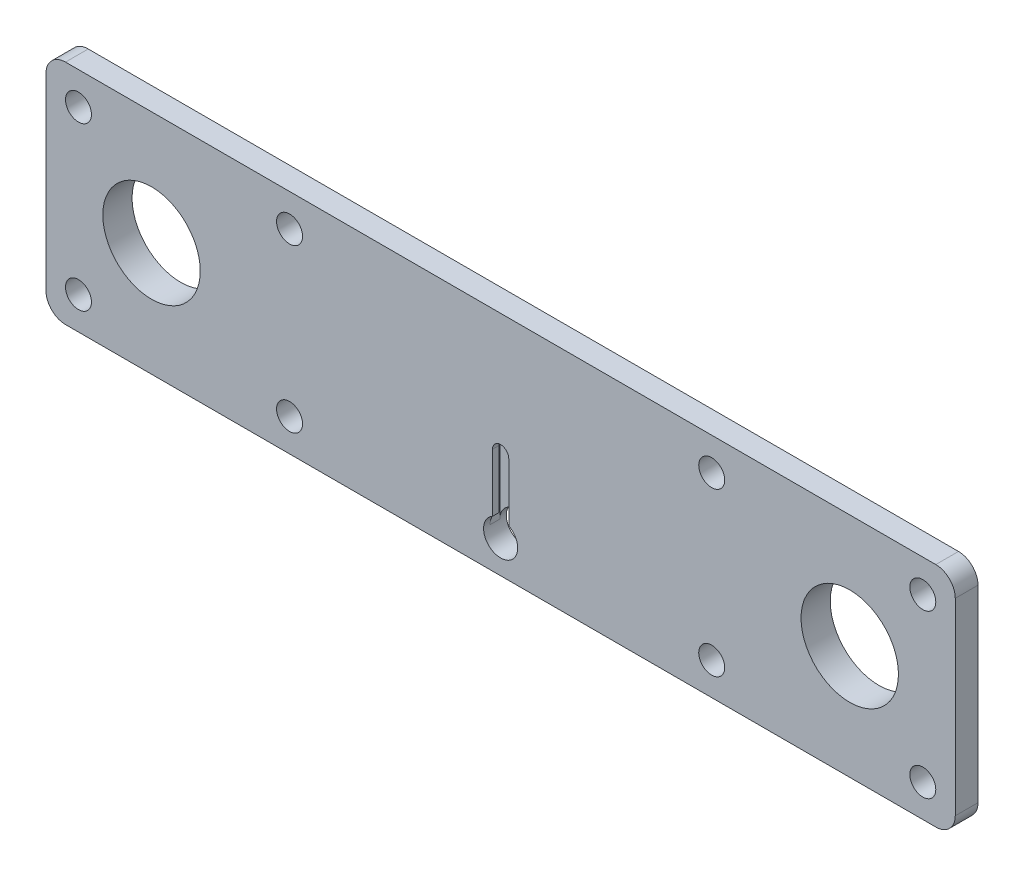
SolidWorks part; units mm, degrees
ref_plane "Ön Düzlem" through (0, 0, 0) normal (0, 0, 1) x (1, 0, 0)
ref_plane "Üst Düzlem" through (0, 0, 0) normal (0, 1, 0) x (1, 0, 0)
ref_plane "Sağ Düzlem" through (0, 0, 0) normal (1, 0, 0) x (0, 0, -1)
sketch "Sketch1" plane through (0, 0, 0) normal (0, 0, 1) x (1, 0, 0)
  line L1 (-140, 35) -> (140, 35)
  line L2 (-140, 35) -> (-140, -35)
  line L3 (-140, -35) -> (140, -35)
  line L4 (140, 35) -> (140, -35)
  line L5 (-140, 35) -> (140, -35) construction
  line L6 (-140, -35) -> (140, 35) construction
  point P0 (0, 0)
  dimension "D1" = 70
  dimension "D2" = 280
extrude "Boss-Extrude1" add sketch "Sketch1" along normal blind 7
fillet "Fillet1" radius 6 4 edges at (140, -35, 3.5) (140, 35, 3.5) (-140, -35, 3.5) (-140, 35, 3.5)
sketch "Sketch2" plane through (0, 0, 0) normal (0, 0, -1) x (-1, 0, 0)
  line L0 (-140, -29) -> (-140, 29) construction
  line L1 (140, 29) -> (140, -29) construction
  line L2 (-134, 35) -> (134, 35) construction
  line L4 (107.5, 0) -> (-107.5, 0) construction
  line L5 (130, 25) -> (0, 25) construction
  line L6 (130, 25) -> (130, -25) construction
  line L7 (130, -25) -> (-130, -25) construction
  line L8 (-130, 25) -> (-130, -25) construction
  line L9 (130, 25) -> (-130, -25) construction
  line L10 (130, -25) -> (-130, 25) construction
  line L15 (0, -2.5) -> (0, -19.75) construction
  line L18 (2.5, -2.5) -> (2.5, -20.3835)
  line L19 (-2.5, -2.5) -> (-2.5, -20.3835)
  circle A0 centre (-107.5, 0) radius 15
  circle A1 centre (107.5, 0) radius 15
  circle A2 centre (130, 25) radius 4
  circle A3 centre (65, 25) radius 4
  circle A5 centre (-65, 25) radius 4
  circle A6 centre (-130, 25) radius 4
  circle A7 centre (-130, -25) radius 4
  circle A8 centre (-65, -25) radius 4
  circle A10 centre (65, -25) radius 4
  circle A11 centre (130, -25) radius 4
  arc A12 (-2.5, -2.5) -> (2.5, -2.5) centre (0, -2.5) cw
  arc A13 (2.5, -20.3835) -> (-2.5, -20.3835) centre (0, -25) cw
  arc A20 (2.6458, 22) -> (-2.6458, 22) centre (0, 25) ccw [skipped]
  point P9 (140, 0)
  point P10 (0, 0)
  point P29 (0, 0)
  point P45 (0, -12.5)
  dimension "D1" = 32.5
  dimension "D2" = 30
  dimension "D3" = 32.5
  dimension "D4" = 30
  dimension "D5" = 10
  dimension "D6" = 10
  dimension "D7" = 8
  dimension "D8" = 5
extrude "Cut-Extrude1" cut sketch "Sketch2" against normal blind 10
sketch "Sketch3" plane through (0, 0, 0) normal (0, 0, -1) x (-1, 0, 0)
  circle A0 centre (-107.5, 0) radius 15
  circle A1 centre (-107.5, 0) radius 20
  circle A2 centre (107.5, 0) radius 15
  circle A3 centre (107.5, 0) radius 20
  dimension "D1" = 40
  dimension "D2" = 40
extrude "Boss-Extrude2" add sketch "Sketch3" along normal blind 2
ref_plane "Plane1" through (0, 0, 2) normal (0, 0, -1) x (-1, 0, 0)
sketch "Sketch4" plane through (0, 0, 2) normal (0, 0, -1) x (-1, 0, 0)
  line L1 (0, -25) -> (5.25, -25)
  line L2 (-5.25, -25) -> (-5.25, -2.5)
  line L9 (5.25, -2.5) -> (5.25, -25)
  line L10 (0, -25) -> (-5.25, -25)
  arc A0 (-5.25, -2.5) -> (5.25, -2.5) centre (0, -2.5) cw
extrude "Cut-Extrude2" cut sketch "Sketch4" against normal blind 3
